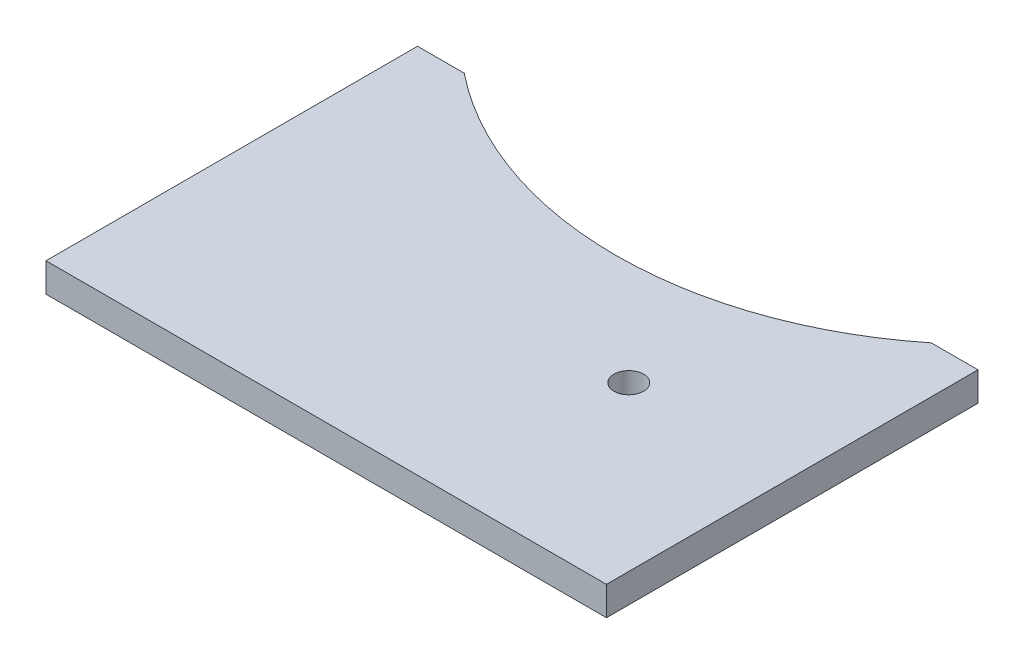
SolidWorks part; units mm, degrees
material "Polietileno reticulado"
ref_plane "Alzado" through (0, 0, 0) normal (0, 0, 1) x (1, 0, 0)
ref_plane "Planta" through (0, 0, 0) normal (0, 1, 0) x (1, 0, 0)
ref_plane "Vista lateral" through (0, 0, 0) normal (1, 0, 0) x (0, 0, -1)
sketch "Croquis1" plane through (0, 0, 0) normal (0, 1, 0) x (1, 0, 0)
  line L0 (0, 0) -> (0, -79.55)
  line L1 (0, -79.55) -> (120, -79.55)
  line L2 (120, -79.55) -> (120, 0)
  line L3 (120, 0) -> (110, 0)
  line L4 (0, 0) -> (10, 0)
  arc A0 (10, 0) -> (110, 0) centre (60, 62.45) ccw
  point P3 (60, -17.55)
  point P9 (60, -79.55)
  dimension "D5" = 80
  dimension "D1" = 10
  dimension "D2" = 10
  dimension "D3" = 120
  dimension "D4" = 62
extrude "Saliente-Extruir1" add sketch "Croquis1" along normal blind 6.2
ref_plane "Plano1" through (60, 0, 0) normal (1, 0, 0) x (0, 0, -1)
sketch "Croquis2" plane through (0, 6.2, 0) normal (0, 1, 0) x (1, 0, 0)
  line L0 (-19.112, -39.775) -> (189.112, -39.775) construction
  line L1 (0, 0) -> (0, -79.55) construction
  line L2 (60, -79.55) -> (60, -17.55) construction
  line L3 (0, -79.55) -> (120, -79.55) construction
  circle A0 centre (85, -39.775) radius 3.175
  arc A1 (10, 0) -> (110, 0) centre (60, 62.45) ccw construction
  point P4 (0, -39.775)
  dimension "D1" = 6.35
  dimension "D2" = 25
extrude "Cortar-Extruir1" cut sketch "Croquis2" against normal through all
sketch "Croquis3" plane through (0, 6.2, 0) normal (0, 1, 0) x (1, 0, 0)
  point P0 (60, -17.55)
